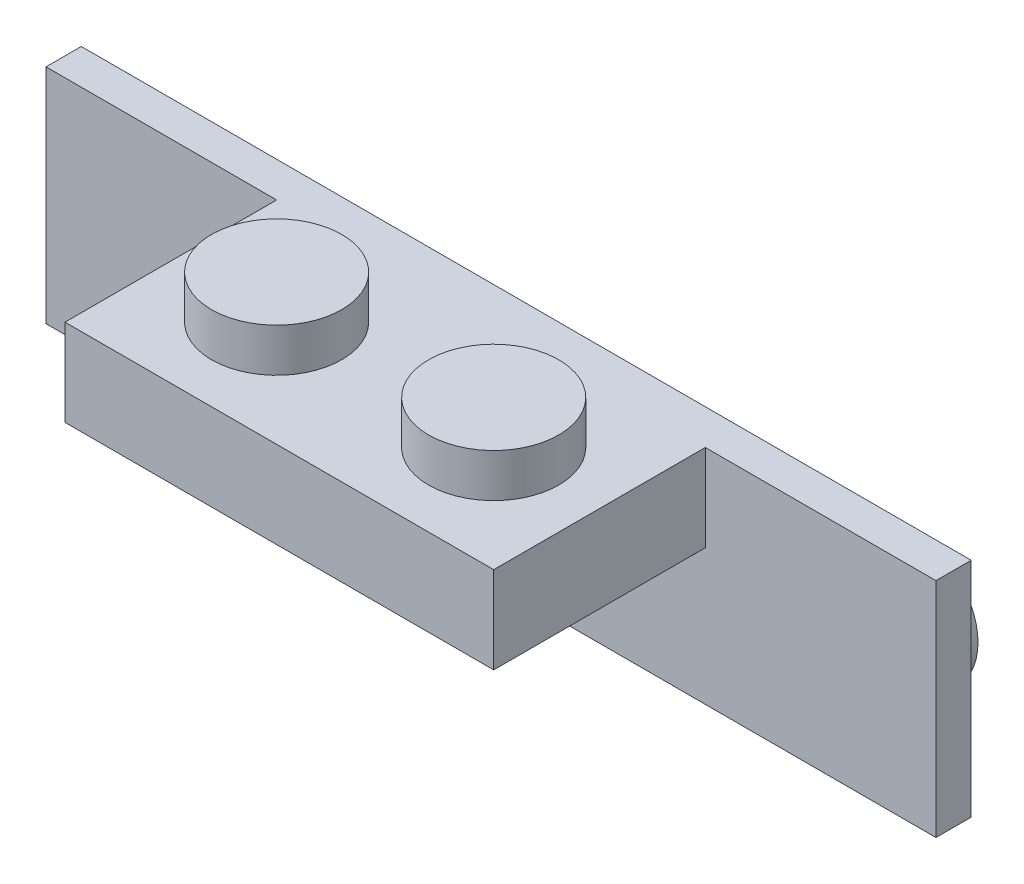
SolidWorks part; units mm, degrees
material "ABS"
ref_plane "Front Plane" through (0, 0, 0) normal (0, 0, 1) x (1, 0, 0)
ref_plane "Top Plane" through (0, 0, 0) normal (0, 1, 0) x (1, 0, 0)
ref_plane "Right Plane" through (0, 0, 0) normal (1, 0, 0) x (0, 0, -1)
sketch "Sketch1" plane through (0, 0, 0) normal (0, 0, 1) x (1, 0, 0)
  line L1 (0, 0) -> (15.8, 0)
  line L2 (0, 0) -> (0, 3.2)
  line L3 (0, 3.2) -> (15.8, 3.2)
  line L4 (15.8, 0) -> (15.8, 3.2)
  line L5 (0, 0) -> (15.8, 3.2) construction
  line L6 (0, 3.2) -> (15.8, 0) construction
  point P4 (7.9, 1.6)
  dimension "D1" = 15.8
  dimension "D2" = 3.2
extrude "Boss-Extrude1" add sketch "Sketch1" against normal blind 7.8
sketch "Sketch2" plane through (0, 3.2, 0) normal (0, 1, 0) x (1, 0, 0)
  line L0 (15.8, 0) -> (0, 0) construction
  circle A0 centre (3.9, 3.9) radius 2.4
  dimension "D1" = 4.8
  dimension "D2" = 3.9
  dimension "D3" = 3.9
extrude "Boss-Extrude2" add sketch "Sketch2" along normal blind 1.6
pattern_linear "LPattern1" count 2 spacing 8 along (0, 0, 1) count 4 spacing 8 along (1, 0, 0) of "Boss-Extrude2"
shell "Shell1" thickness 1.2
sketch "Sketch3" plane through (0, 2, 0) normal (0, -1, 0) x (1, 0, 0)
  line L0 (0, 0) -> (15.8, 0) construction
  line L1 (0, -7.8) -> (0, 0) construction
  circle A0 centre (7.9, -3.9) radius 1.5
  circle A1 centre (7.9, -3.9) radius 0.6
  dimension "D1" = 3
  dimension "D2" = 1.2
  dimension "D3" = 3.9
  dimension "D4" = 7.9
extrude "Boss-Extrude3" add sketch "Sketch3" along normal offset from surface (1.8 mm away) 0.2 up to face at (7.9, 0, -3.9)
ref_plane "Plane1" through (0, 0, -7.8) normal (0, 0, -1) x (-1, 0, 0)
sketch "Sketch4" plane through (0, 0, -7.8) normal (0, 0, -1) x (-1, 0, 0)
  line L0 (-24.3, 3.2) -> (8.5, 3.2)
  line L1 (8.5, 3.2) -> (8.5, -5)
  line L2 (8.5, -5) -> (-24.3, -5)
  line L3 (-24.3, -5) -> (-24.3, 3.2)
  line L4 (0, 0) -> (-15.8, 0) construction
  line L5 (-15.8, 3.2) -> (0, 3.2) construction
  point P8 (-7.9, 3.2)
  point P9 (-7.9, 3.2)
  dimension "D1" = 5
  dimension "D2" = 8.5
extrude "Boss-Extrude4" add sketch "Sketch4" along normal blind 1.3
sketch "Sketch5" plane through (0, 0, -9.1) normal (0, 0, -1) x (-1, 0, 0)
  line L0 (-24.3, 3.2) -> (-24.3, -5) construction
  line L1 (-24.3, -5) -> (8.5, -5) construction
  circle A0 centre (-20.4, -1.1) radius 2.35
  circle A1 centre (-20.4, -1.1) radius 1.55
  dimension "D3" = 4.7
  dimension "D4" = 0.8
  dimension "D1" = 3.9
  dimension "D2" = 3.9
extrude "Boss-Extrude5" add sketch "Sketch5" along normal blind 1.8
pattern_linear "LPattern2" count 4 spacing 8 along (-1, 0, 0) of "Boss-Extrude5"
